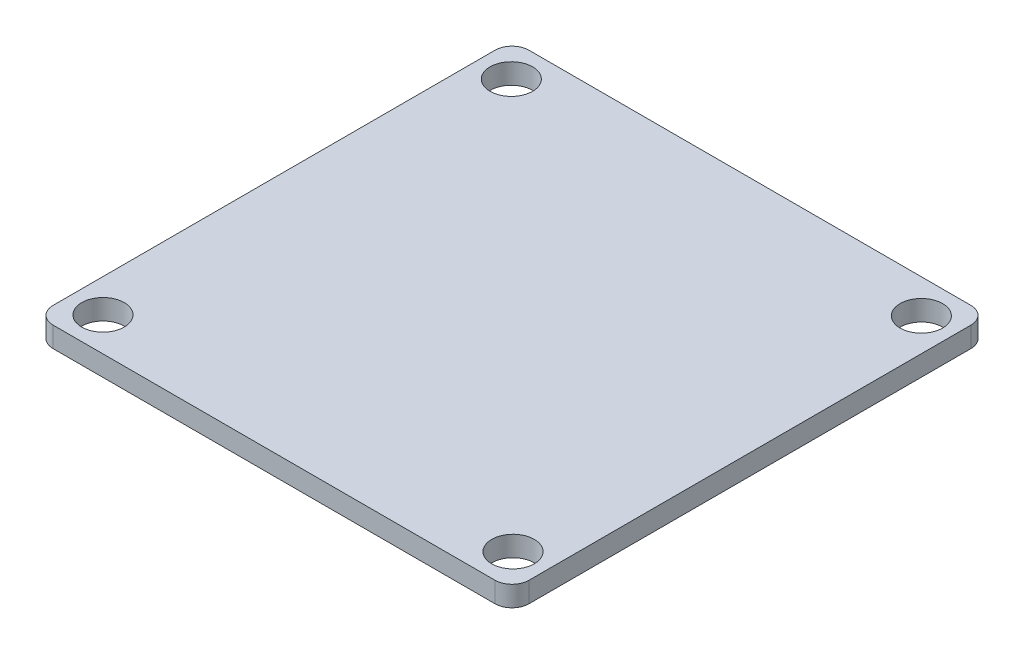
SolidWorks part; units mm, degrees
ref_plane "Front Plane" through (0, 0, 0) normal (0, 0, 1) x (1, 0, 0)
ref_plane "Top Plane" through (0, 0, 0) normal (0, 1, 0) x (1, 0, 0)
ref_plane "Right Plane" through (0, 0, 0) normal (1, 0, 0) x (0, 0, -1)
sketch "Sketch1" plane through (0, 0, 0) normal (0, 1, 0) x (1, 0, 0)
  line L0 (-50.7462, 35.4274) -> (-17.7262, 35.4274)
  line L1 (-52.0162, 34.1574) -> (-52.0162, 1.1374)
  line L2 (-50.7462, -0.1326) -> (-17.7262, -0.1326)
  line L3 (-16.4562, 1.1374) -> (-16.4562, 8.1859)
  line L8 (-16.4562, 27.1089) -> (-16.4562, 8.1859)
  line L11 (-16.4562, 27.1089) -> (-16.4562, 34.1574)
  circle A0 centre (-49.5397, 32.9001) radius 1.5875
  circle A1 centre (-18.9073, 32.9001) radius 1.5875
  circle A2 centre (-18.9073, 2.3947) radius 1.5875
  circle A3 centre (-49.5397, 2.3947) radius 1.5875
  arc A4 (-50.7462, 35.4274) -> (-52.0162, 34.1574) centre (-50.7462, 34.1574) ccw
  arc A5 (-52.0162, 1.1374) -> (-50.7462, -0.1326) centre (-50.7462, 1.1374) ccw
  arc A6 (-17.7262, -0.1326) -> (-16.4562, 1.1374) centre (-17.7262, 1.1374) ccw
  arc A7 (-17.7262, 35.4274) -> (-16.4562, 34.1574) centre (-17.7262, 34.1574) cw
  point P20 (-16.4562, 4.6617)
  point P38 (-16.4562, 25.8389)
  dimension "D1" = 1.27
  dimension "D2" = 30.6324
  dimension "D3" = 3.175
  dimension "D5" = 2.5273
  dimension "D4" = 35.56
extrude "Boss-Extrude2" add sketch "Sketch1" along normal blind 1.524
